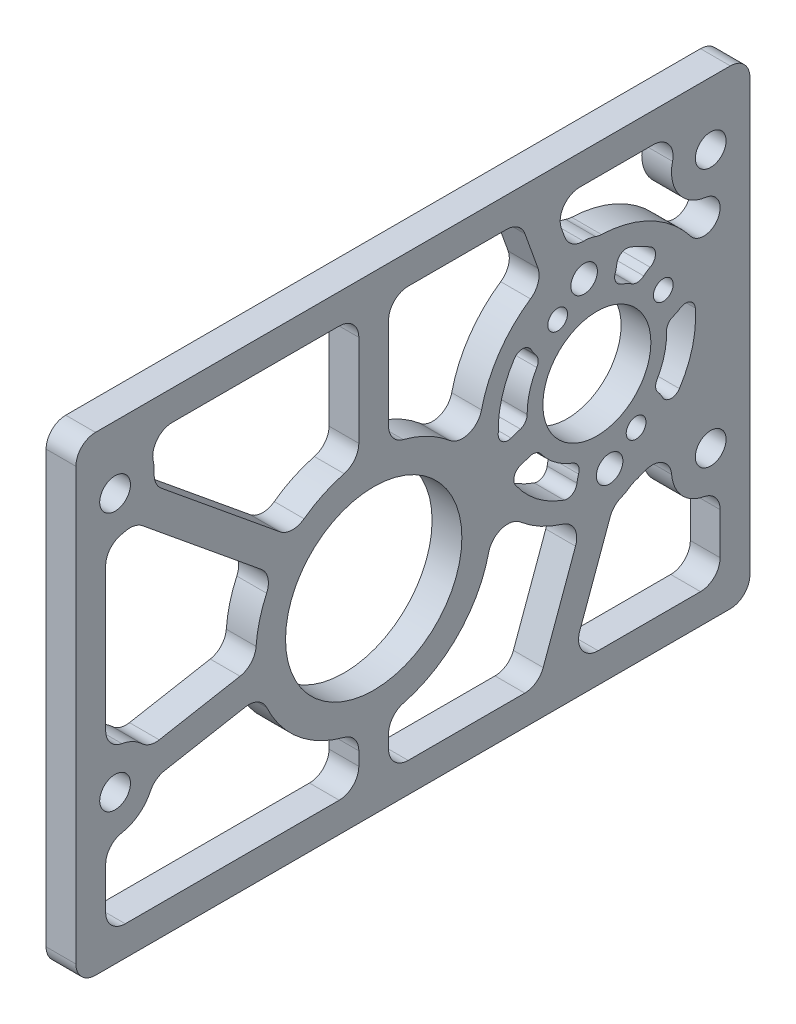
SolidWorks part; units mm, degrees
material "6061-T6 (SS)"
ref_plane "Front Plane" through (0, 0, 0) normal (0, 0, 1) x (1, 0, 0)
ref_plane "Top Plane" through (0, 0, 0) normal (0, 1, 0) x (1, 0, 0)
ref_plane "Right Plane" through (0, 0, 0) normal (1, 0, 0) x (0, 0, -1)
sketch "Sketch2" plane through (0, 0, 0) normal (1, 0, 0) x (0, 0, -1)
  line L0 (38.2297, -2.2861) -> (34.1015, 26.4186) construction
  line L1 (-48.26, 44.45) -> (60.96, 44.45)
  line L2 (-48.26, 44.45) -> (-48.26, -31.75)
  line L3 (-48.26, -31.75) -> (60.96, -31.75)
  line L4 (60.96, 44.45) -> (60.96, -31.75)
  line L5 (25.4019, 5.7108) -> (42.5211, 1.3025) construction
  line L6 (42.5211, 1.3025) -> (46.9293, 18.4218) construction
  line L7 (46.9293, 18.4218) -> (29.8101, 22.83) construction
  line L8 (29.8101, 22.83) -> (25.4019, 5.7108) construction
  circle A0 centre (0, 0) radius 14.2875
  circle A1 centre (0, 0) radius 33.0327 construction
  circle A2 centre (36.1656, 12.0663) radius 5.0927 construction
  circle A3 centre (36.1656, 12.0663) radius 22.5 construction
  circle A4 centre (36.1656, 12.0663) radius 8.75
  circle A5 centre (36.1656, 12.0663) radius 12.5 construction
  circle A10 centre (82.55, 0) radius 19.9136 construction
  circle A14 centre (54.61, 34.29) radius 2.4892
  circle A15 centre (54.61, 34.29) radius 6.35 construction
  circle A16 centre (54.61, -7.62) radius 2.4892
  circle A17 centre (54.61, -7.62) radius 6.35 construction
  circle A18 centre (54.61, -7.62) radius 4.4768 construction
  circle A19 centre (29.8101, 22.83) radius 1.6 construction
  circle A20 centre (34.1015, 26.4186) radius 2.15 construction
  circle A21 centre (38.2297, -2.2861) radius 2.15 construction
  circle A31 centre (-41.91, 34.29) radius 2.4892
  circle A32 centre (-41.91, -7.62) radius 2.4892
  circle A33 centre (-41.91, 34.29) radius 6.35 construction
  point P31 (36.1656, 12.0663)
  point P33 (36.1656, 34.5663)
  dimension "D1" = 28.575
  dimension "D2" = 66.0654
  dimension "D3" = 10.1854
  dimension "D4" = 45
  dimension "D9" = 17.5
  dimension "D10" = 25
  dimension "D12" = 4.9784
  dimension "D16" = 39.8272
  dimension "D20" = 38.298
  dimension "D22" = 37.548
  dimension "D13" = 12.7
  dimension "D17" = 8.9535
  dimension "D19" = 3.2
  dimension "D21" = 4.3
  dimension "D5" = 31.75
  dimension "D6" = 76.2
  dimension "D7" = 109.22
  dimension "D8" = 48.26
  dimension "D11" = 10.16
  dimension "D14" = 24.13
  dimension "D15" = 82.55
  dimension "D18" = 29
extrude "Boss-Extrude1" add sketch "Sketch2" against normal blind 4.826
hole_wizard "M3 Clearance Hole1" positions "Sketch3" profile "Sketch4" hole size "M3" standard "ANSI Metric" end condition through all
sketch "Sketch3" plane through (0, 0, 0) normal (1, 0, 0) x (0, 0, -1)
  point P0 (42.5211, 1.3025)
  point P3 (29.8101, 22.83)
  point P13 (46.9293, 18.4218)
sketch "Sketch4" plane through (0, 1.3025, -42.5211) normal (0, 1, 0) x (0, 0, -1)
  line L0 (0, 0) -> (0, 4.826)
  line L1 (0, 4.826) -> (1.6, 4.826)
  line L2 (1.6, 4.826) -> (1.6, 0)
  line L5 (1.6, 0) -> (0, 0)
  line L11 (0, -6.35) -> (0, 107.95) construction
  dimension "Thru Hole Dia." = 3.2
  dimension "Thru Hole Depth" = 4.826
hole_wizard "M4 Clearance Hole2" positions "Sketch5" profile "Sketch6" hole size "M4" standard "ANSI Metric" end condition through all
sketch "Sketch5" plane through (0, 0, 0) normal (1, 0, 0) x (0, 0, -1)
  point P0 (34.1015, 26.4186)
  point P3 (38.2297, -2.2861)
sketch "Sketch6" plane through (0, 26.4186, -34.1015) normal (0, 1, 0) x (0, 0, -1)
  line L0 (0, 0) -> (0, 4.826)
  line L1 (0, 4.826) -> (2.15, 4.826)
  line L2 (2.15, 4.826) -> (2.15, 0)
  line L5 (2.15, 0) -> (0, 0)
  line L11 (0, -6.35) -> (0, 107.95) construction
  dimension "Thru Hole Dia." = 4.3
  dimension "Thru Hole Depth" = 4.826
sketch "Sketch7" plane through (0, 0, 0) normal (1, 0, 0) x (0, 0, -1)
  line L0 (0, 0) -> (36.1656, 12.0663) construction
  line L1 (-0.7637, 2.289) -> (35.4019, 14.3552)
  line L2 (0.7637, -2.289) -> (36.9293, 9.7773)
  line L3 (0, 0) -> (-41.91, -7.62) construction
  line L4 (60.96, -31.75) -> (60.96, 44.45) construction
  line L5 (0.4317, -2.3741) -> (-41.4783, -9.9941)
  line L6 (-0.4317, 2.3741) -> (-42.3417, -5.2459)
  line L7 (0, 0) -> (-41.91, 34.29) construction
  line L8 (56.134, -26.924) -> (56.134, 39.624)
  line L9 (-43.434, -26.924) -> (56.134, -26.924)
  line L10 (-43.434, 39.624) -> (-43.434, -26.924)
  line L11 (56.134, 39.624) -> (-43.434, 39.624)
  line L12 (56.134, -26.924) -> (56.134, 39.624)
  line L13 (-43.434, -26.924) -> (56.134, -26.924)
  line L14 (-43.434, 39.624) -> (-43.434, -26.924)
  line L15 (56.134, 39.624) -> (-43.434, 39.624)
  line L16 (-1.528, -1.8676) -> (-43.438, 32.4224)
  line L17 (1.528, 1.8676) -> (-40.382, 36.1576)
  line L18 (0, 0) -> (0, -26.924) construction
  line L19 (2.413, 0) -> (2.413, -26.924)
  line L20 (-2.413, 0) -> (-2.413, -26.924)
  line L21 (0, 0) -> (0, 39.624) construction
  line L22 (-2.413, 0) -> (-2.413, 39.624)
  line L23 (2.413, 0) -> (2.413, 39.624)
  line L24 (46.9293, 18.4218) -> (56.134, 18.4218) construction
  line L25 (46.9293, 20.8348) -> (56.134, 20.8348)
  line L26 (46.9293, 16.0088) -> (56.134, 16.0088)
  line L27 (54.61, -7.62) -> (42.5211, 1.3025) construction
  line L28 (53.1771, -9.5615) -> (41.0881, -0.6389)
  line L29 (56.0429, -5.6785) -> (43.954, 3.244)
  line L30 (38.2297, -2.2861) -> (29.2735, -26.924) construction
  line L33 (36.1656, 12.0663) -> (24.6033, 44.45) construction
  line L34 (33.8931, 11.2549) -> (22.3308, 43.6386)
  line L35 (38.4381, 12.8777) -> (26.8758, 45.2614)
  line L36 (31.0375, 23.8564) -> (32.4522, 25.0394) construction
  line L37 (40.4975, -3.1104) -> (31.5413, -27.7484)
  line L38 (35.9619, -1.4617) -> (27.0057, -26.0996)
  line L42 (27.0057, -26.0996) -> (24.9517, -31.75)
  line L43 (-48.26, -31.75) -> (60.96, -31.75) construction
  line L44 (60.96, 44.45) -> (-48.26, 44.45) construction
  circle A0 centre (-41.91, 34.29) radius 6.35
  circle A1 centre (-41.91, -7.62) radius 6.35
  circle A2 centre (54.61, -7.62) radius 6.35
  circle A3 centre (54.61, 34.29) radius 6.35
  circle A4 centre (0, 0) radius 19.1135
  circle A5 centre (36.1656, 12.0663) radius 16
  circle A6 centre (0, 0) radius 14.2875 construction
  circle A7 centre (53.4807, 25.3578) radius 2.6533
  circle A8 centre (34.1015, 26.4186) radius 5.325
  circle A9 centre (46.9293, 18.4218) radius 4.775
  circle A10 centre (29.8101, 22.83) radius 4.775
  circle A11 centre (42.5211, 1.3025) radius 4.775
  circle A12 centre (38.2297, -2.2861) radius 5.325
  circle A13 centre (46.9293, 18.4218) radius 1.6 construction
  arc A14 (-0.7637, 2.289) -> (0.7637, -2.289) centre (0, 0) ccw
  circle A15 centre (34.1015, 26.4186) radius 2.15 construction
  arc A16 (36.9293, 9.7773) -> (35.4019, 14.3552) centre (36.1656, 12.0663) ccw
  arc A17 (0.4317, -2.3741) -> (-0.4317, 2.3741) centre (0, 0) ccw
  arc A18 (-42.3417, -5.2459) -> (-41.4783, -9.9941) centre (-41.91, -7.62) ccw
  arc A19 (-1.528, -1.8676) -> (1.528, 1.8676) centre (0, 0) ccw
  arc A20 (-40.382, 36.1576) -> (-43.438, 32.4224) centre (-41.91, 34.29) ccw
  arc A21 (2.413, 0) -> (-2.413, 0) centre (0, 0) ccw
  arc A22 (-2.413, -26.924) -> (2.413, -26.924) centre (0, -26.924) ccw
  arc A23 (-2.413, 0) -> (2.413, 0) centre (0, 0) ccw
  arc A24 (2.413, 39.624) -> (-2.413, 39.624) centre (0, 39.624) ccw
  arc A25 (46.9293, 20.8348) -> (46.9293, 16.0088) centre (46.9293, 18.4218) ccw
  arc A26 (56.134, 16.0088) -> (56.134, 20.8348) centre (56.134, 18.4218) ccw
  arc A27 (53.1771, -9.5615) -> (56.0429, -5.6785) centre (54.61, -7.62) ccw
  arc A28 (43.954, 3.244) -> (41.0881, -0.6389) centre (42.5211, 1.3025) ccw
  arc A31 (33.8931, 11.2549) -> (38.4381, 12.8777) centre (36.1656, 12.0663) ccw
  arc A32 (26.8758, 45.2614) -> (22.3308, 43.6386) centre (24.6033, 44.45) ccw
  circle A33 centre (29.8101, 22.83) radius 1.6 construction
  arc A34 (40.4975, -3.1104) -> (35.9619, -1.4617) centre (38.2297, -2.2861) ccw
  arc A35 (27.0057, -26.0996) -> (31.5413, -27.7484) centre (29.2735, -26.924) ccw
  arc A36 (2.413, -26.924) -> (56.134, -26.924) centre (29.2735, -26.924) ccw construction
  arc A39 (26.706, -26.924) -> (34.3402, -5.923) centre (30.5231, -16.4235) cw construction
  circle A40 centre (36.1656, 12.0663) radius 11.3
  circle A41 centre (36.1656, 12.0663) radius 19.175
  circle A42 centre (21.7227, -4.9902) radius 3.175
  circle A43 centre (14.3746, 17.0337) radius 3.175
  circle A44 centre (45.118, -8.4124) radius 3.175
  circle A45 centre (50.535, 13.1796) radius 1.5875
  circle A46 centre (48.2102, 4.1513) radius 1.5875
  point P47 (18.0828, 6.0331)
  point P53 (-20.955, -3.81)
  point P59 (-20.955, 17.145)
  point P67 (0, -13.462)
  point P74 (0, 19.812)
  point P79 (51.5317, 18.4218)
  point P85 (48.5655, -3.1587)
  point P90 (33.7516, -14.605)
  point P98 (30.3844, 28.2581)
  point P107 (31.7449, 24.4479)
  dimension "D2" = 4.826
  dimension "D3" = 32
  dimension "D4" = 3.175
  dimension "D5" = 3.175
  dimension "D6" = 4.826
  dimension "D7" = 22.6
  dimension "D8" = 3.175
  dimension "D9" = 6.35
  dimension "D10" = 3.175
  dimension "D1" = 4.826
extrude "Cut-Extrude1" cut sketch "Sketch7" against normal through all contours A4 L16 A0 L14 A1 L6 | A4 L22 L15 A0 L17 | A4 L5 A1 L14 L13 L20 | A4 L19 L13 L38 | A41 L34 L15 L23 A4 | A40 A11 L29 A5 L26 A9 | A40 L2 A5 A12 | A40 A10 A5 L1 | A40 A9 A5 A8 | A41 L37 L13 L12 A2 L28 | A41 A7 A3 L15 L35 | A7 | A43 | A42 | A44 | A45 | A46
fillet "Fillet1" radius 3.175 34 edges at (-2.413, -26.924, -26.706) (-2.413, -18.9606, -2.413) (-2.413, -26.924, -2.413) (-2.413, -26.924, 2.413) (-2.413, -18.9606, 2.413) (-2.413, -5.7658, 18.2231) (-2.413, -26.924, 43.434) (-2.413, -13.7844, 43.434) (-2.413, -1.4556, 43.434) (-2.413, -8.9434, 35.6994) (-2.413, -4.1952, 36.5627) (-2.413, -1.0177, 19.0864) (-2.413, 10.139, 16.2027) (-2.413, 13.8741, 13.1467) (-2.413, 18.9606, 2.413) (-2.413, 39.624, 2.413) (-2.413, 32.4381, 35.836) (-2.413, 39.624, 38.4646) (-2.413, 28.703, 38.892) (-2.413, 28.1256, 43.434) (-2.413, -13.7844, -56.134) (-2.413, 39.624, -51.1646) (-2.413, 31.2563, -31.8762) (-2.413, 39.624, -28.8885) (-2.413, 39.624, -23.7642) (-2.413, 39.624, -2.413) (-2.413, 18.9606, -2.413) (-2.413, -26.924, -56.134) (-2.413, -26.924, -31.841) (-2.413, -7.5717, -38.8758) (-2.413, 29.1698, -27.4967) (-2.413, -6.9809, -33.9556) (-2.413, 31.2403, -36.3614) (-2.413, -6.2755, -41.7568)
fillet "Fillet3" radius 1.5875 14 edges at (-2.413, -3.633, -33.0779) (-2.413, 4.7714, -21.9254) (-2.413, 6.2835, -26.4574) (-2.413, 0.9722, -34.0179) (-2.413, 5.2632, -45.1883) (-2.413, 21.0889, -42.9687) (-2.413, 13.6655, -47.3519) (-2.413, 23.1302, -47.7237) (-2.413, 27.7655, -39.2533) (-2.413, 23.1603, -38.3133) (-2.413, 10.8614, -24.93) (-2.413, 9.3493, -20.398) (-2.413, 18.8693, -27.143) (-2.413, 23.6243, -25.1017)
fillet "Fillet4" radius 3.175 4 edges at (-2.413, 44.45, -60.96) (-2.413, -31.75, -60.96) (-2.413, -31.75, 48.26) (-2.413, 44.45, 48.26)
